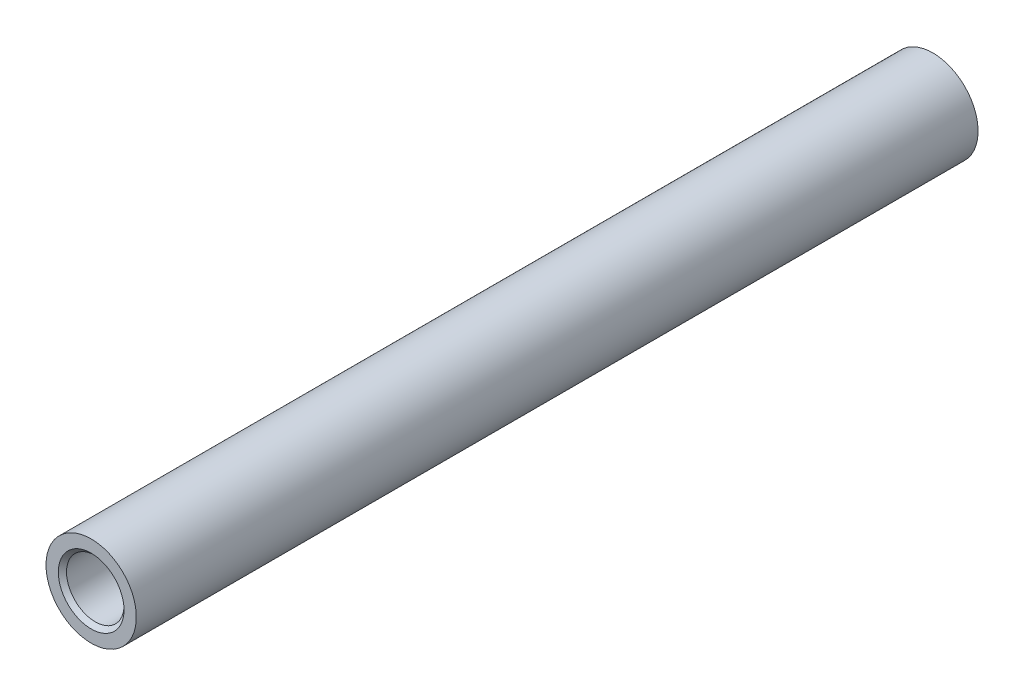
SolidWorks part; units mm, degrees
material "1.0545 (S355N)"
ref_plane "Płaszczyzna przednia" through (0, 0, 0) normal (0, 0, 1) x (1, 0, 0)
ref_plane "Płaszczyzna górna" through (0, 0, 0) normal (0, 1, 0) x (1, 0, 0)
ref_plane "Płaszczyzna prawa" through (0, 0, 0) normal (1, 0, 0) x (0, 0, -1)
sketch "Szkic1" plane through (0, 0, 0) normal (0, 0, 1) x (1, 0, 0)
  circle A0 centre (0, 0) radius 11
  circle A1 centre (0, 0) radius 7
  dimension "D1" = 22
  dimension "D2" = 4
extrude "Dodanie-wyciągnięcie1" add sketch "Szkic1" along normal mid plane 205
sketch "Szkic2" plane through (0, 0, -102.5) normal (0, 0, -1) x (-1, 0, 0)
  circle A0 centre (0, 0) radius 8
  circle A1 centre (0, 0) radius 7 construction
  dimension "D1" = 1
extrude "Wytnij-wyciągnięcie1" cut sketch "Szkic2" against normal blind 50
chamfer "Sfazowanie1" distance 1 angle 45 1 edges at (7, 0, 102.5)
